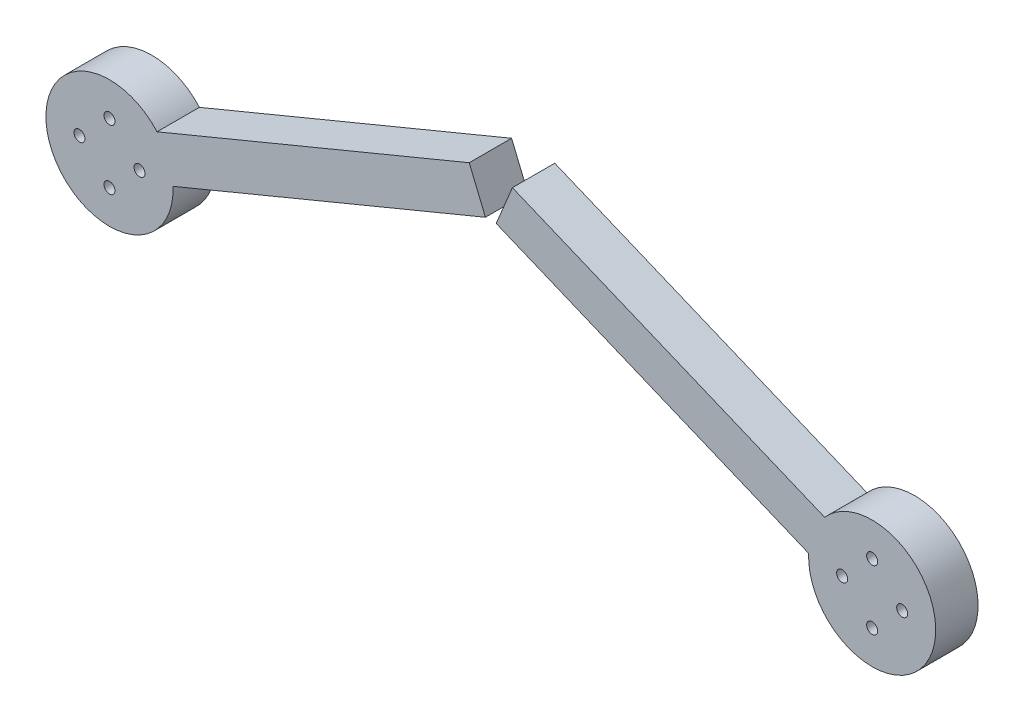
SolidWorks part; units mm, degrees
ref_plane "Front Plane" through (0, 0, 0) normal (0, 0, 1) x (1, 0, 0)
ref_plane "Top Plane" through (0, 0, 0) normal (0, 1, 0) x (1, 0, 0)
ref_plane "Right Plane" through (0, 0, 0) normal (1, 0, 0) x (0, 0, -1)
sketch "Sketch1" plane through (0, 0, 0) normal (0, 0, 1) x (1, 0, 0)
  line L0 (-216.0578, -96.9368) -> (-12.9419, -12.8035)
  line L1 (-216.0578, -96.9368) -> (-206.3377, -120.4034)
  line L2 (-12.9419, -12.8035) -> (-3.2218, -36.27)
  line L3 (-206.3377, -120.4034) -> (-3.2218, -36.27)
  line L4 (12.9419, -12.8035) -> (216.0578, -96.9368)
  line L5 (12.9419, -12.8035) -> (3.2218, -36.27)
  line L6 (216.0578, -96.9368) -> (206.3377, -120.4034)
  line L7 (3.2218, -36.27) -> (206.3377, -120.4034)
  line L8 (-12.9419, -12.8035) -> (0, -7.4427)
  line L9 (0, -7.4427) -> (12.9419, -12.8035)
  line L10 (0, 19.4566) -> (0, -8.1997) construction
  line L11 (-228.6, -115.5981) -> (-228.6, -77.4981) construction
  line L12 (228.6, -115.5981) -> (228.6, -77.4981) construction
  circle A0 centre (-228.6, -115.5981) radius 38.1
  circle A3 centre (-228.6, -115.5981) radius 85.471 construction
  circle A4 centre (228.6, -115.5981) radius 38.1
  circle A5 centre (228.6, -115.5981) radius 85.471 construction
  point P16 (-228.6, -97.5981)
  point P17 (228.6, -97.5981)
  dimension "D5" = 76.2
  dimension "D6" = 170.942
  dimension "D1" = 135
  dimension "D2" = 25.4
  dimension "D3" = 25.4
  dimension "D4" = 18
  dimension "D7" = 18
  dimension "D8" = 457.2
extrude "Boss-Extrude1" add sketch "Sketch1" along normal blind 25.4 contours L0 A0 L3 L1 | L3 A0 L0 L1 | A0 L3 L2 L0 | A4 L4 L5 L7 | L4 A4 L7 L6 | L7 A4 L4 L6
hole_wizard "M6 Clearance Hole1" positions "3DSketch2" profile "Sketch3" hole size "M6" standard "ANSI Metric" end condition through all
sketch3d "3DSketch2"
  point P2 (-228.6, -97.5981, 0)
sketch "Sketch3" plane through (-228.6, -97.5981, 0) normal (1, 0, 0) x (0, 1, 0)
  line L0 (0, 0) -> (0, 25.4)
  line L1 (0, 25.4) -> (3.3, 25.4)
  line L2 (3.3, 25.4) -> (3.3, 0)
  line L5 (3.3, 0) -> (0, 0)
  line L11 (0, -6.35) -> (0, 107.95) construction
  dimension "Thru Hole Dia." = 6.6
  dimension "Thru Hole Depth" = 25.4
pattern_circular "CirPattern1" count 4 over 360 about axis through (-228.6, -115.5981, 0) along (0, 0, 1) of "M6 Clearance Hole1"
mirror "Mirror3" about plane through (0, 0, 0) normal (1, 0, 0) of "CirPattern1", "M6 Clearance Hole1"
equation "\"Rover_Length\"= 25in"
equation "\"Rover_Width\"= 18in"
equation "\"Rover_Height\"= 12in"
equation "\"Chassis_Wheelbase\"= 18in"
equation "\"Chassis_WheelDiam\"= 171mm"
equation "\"Chassis_ArmDiamWidth\"= 0.75in"
equation "\"Chassis_ArmAngle\"= 135deg"
equation "\"Chassis_HubMountOD\"= 3in"
equation "\"Chassis_WheelBoltHole\"= 36mm"
equation "\"Chassis_WheelBoltNum\"= 4"
equation "\"Chassis_DiffBarLength\"= 12in"
equation "\"Chassis_DiffBarWidth\"= 1in"
equation "\"Chassis_DiffBarHeight\"= 0.5in"
equation "\"Chassis_DiffLinkage_Length\"= 2.5in"
equation "\"D1@Sketch1\"=\"Chassis_ArmAngle\""
equation "\"D2@Sketch1\"=\"Chassis_DiffBarWidth\""
equation "\"D3@Sketch1\"=\"Chassis_DiffBarWidth\""
equation "\"D5@Sketch1\"=\"Chassis_HubMountOD\""
equation "\"D4@Sketch1\"=\"Chassis_WheelBoltHole\"/2"
equation "\"D7@Sketch1\"=\"Chassis_WheelBoltHole\"/2"
equation "\"D8@Sketch1\"=\"Chassis_Wheelbase\""
equation "\"D1@Boss-Extrude1\"=\"Chassis_DiffBarWidth\""
